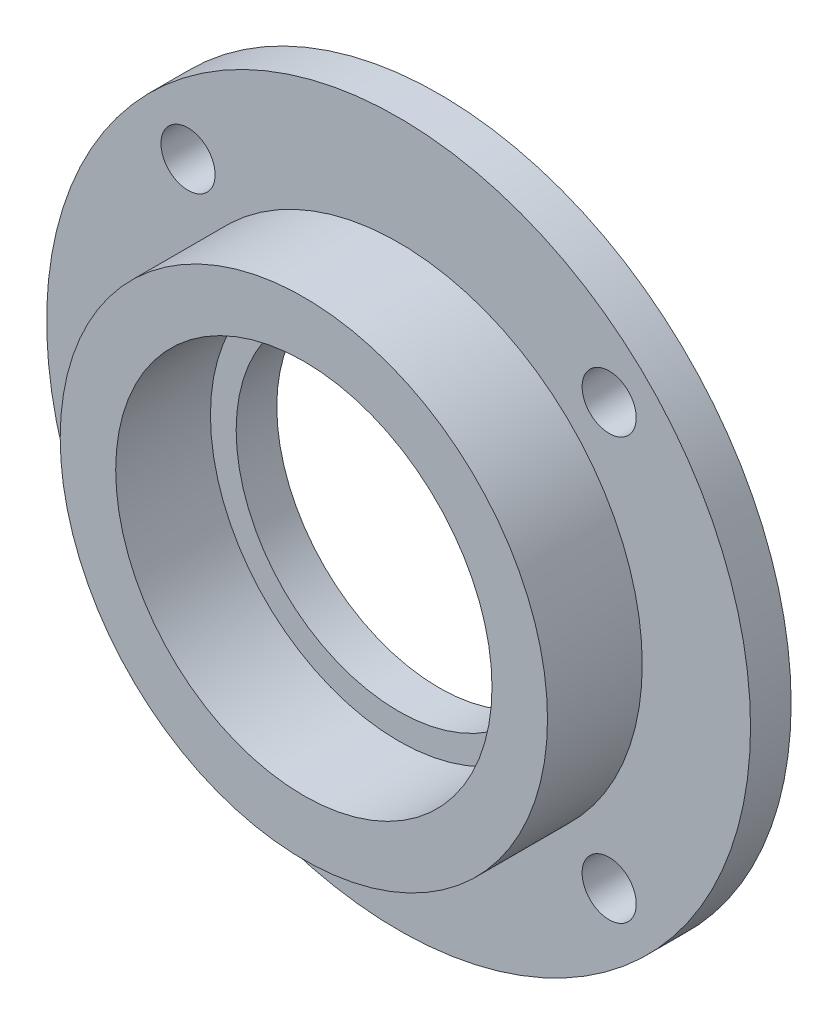
SolidWorks part; units mm, degrees
other "标注1"
sketch "草图6" plane through (-25, -25, 16) normal (-0.0241, -0.4471, 0.8941) x (-0.7339, -0.5994, -0.3195)
material "6061 合金"
ref_plane "前视基准面" through (0, 0, 0) normal (0, 0, 1) x (1, 0, 0)
ref_plane "上视基准面" through (0, 0, 0) normal (0, 1, 0) x (1, 0, 0)
ref_plane "右视基准面" through (0, 0, 0) normal (1, 0, 0) x (0, 0, -1)
sketch "草图1" plane through (0, 0, 0) normal (0, 0, 1) x (1, 0, 0)
  line L0 (0, 0) -> (-21.574, 21.574) construction
  circle A0 centre (0, 0) radius 14 construction
  circle A1 centre (0, 0) radius 12
  circle A2 centre (0, 0) radius 26
  circle A3 centre (0, 0) radius 22 construction
  circle A4 centre (-15.5563, 15.5563) radius 2
  circle A5 centre (15.5563, 15.5563) radius 2
  circle A6 centre (15.5563, -15.5563) radius 2
  circle A7 centre (-15.5563, -15.5563) radius 2
  point P18 (0, 0)
  dimension "D1" = 4
extrude "凸台-拉伸1" add sketch "草图1" along normal blind 3
sketch "草图2" plane through (0, 0, 3) normal (0, 0, 1) x (1, 0, 0)
  circle A0 centre (0, 0) radius 13.9
  circle A1 centre (0, 0) radius 18
extrude "凸台-拉伸2" add sketch "草图2" along normal blind 7
sketch "草图3" plane through (0, 0, 0) normal (0, 0, -1) x (-1, 0, 0)
  circle A0 centre (0, 0) radius 14 construction
  circle A1 centre (0, 14) radius 1.5
  circle A2 centre (14, 0) radius 1.5
  circle A3 centre (0, -14) radius 1.5
  circle A4 centre (-14, 0) radius 1.5
  point P14 (0, 0)
  dimension "D1" = 4
